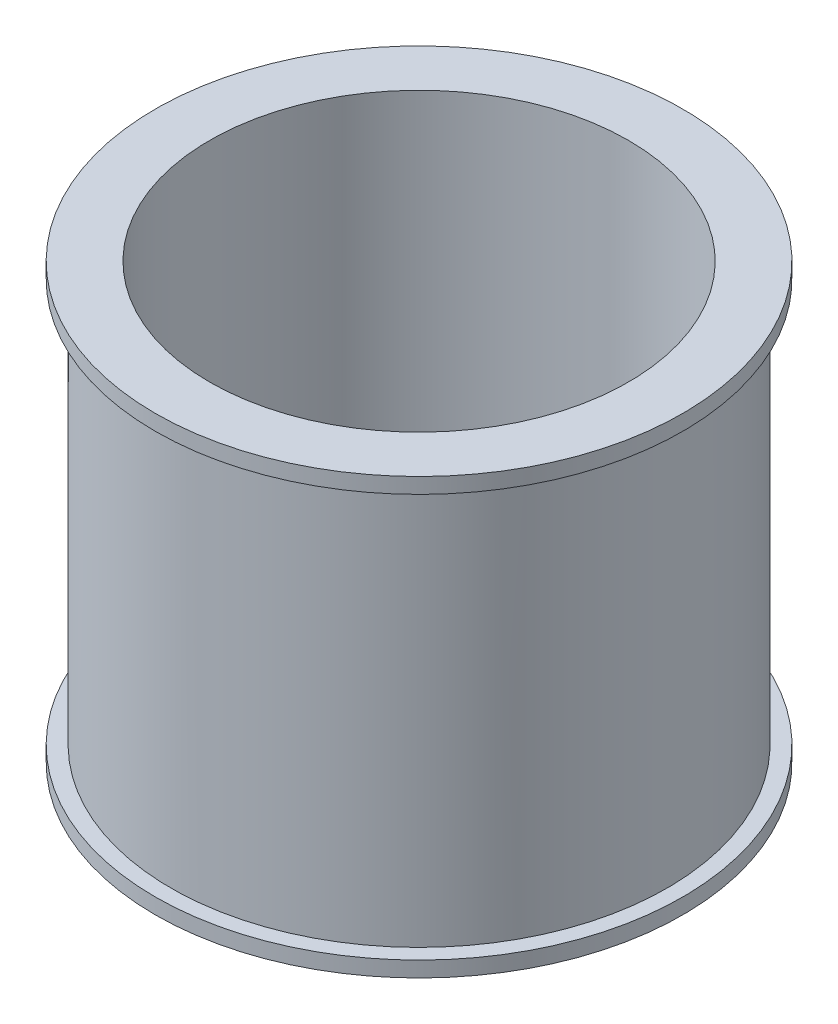
SolidWorks part; units mm, degrees
ref_plane "Front Plane" through (0, 0, 0) normal (0, 0, 1) x (1, 0, 0)
ref_plane "Top Plane" through (0, 0, 0) normal (0, 1, 0) x (1, 0, 0)
ref_plane "Right Plane" through (0, 0, 0) normal (1, 0, 0) x (0, 0, -1)
sketch "Sketch1" plane through (0, 0, 0) normal (0, 1, 0) x (1, 0, 0)
  circle A0 centre (0, 0) radius 4
  dimension "D1" = 8
extrude "Boss-Extrude1" add sketch "Sketch1" along normal blind 7
sketch "Sketch2" plane through (0, 7, 0) normal (0, 1, 0) x (1, 0, 0)
  circle A0 centre (0, 0) radius 3.375
  dimension "D1" = 6.75
extrude "Cut-Extrude1" cut sketch "Sketch2" against normal blind 10 contours A0
sketch "Sketch16" plane through (0, 7, 0) normal (0, 1, 0) x (1, 0, 0)
  circle A0 centre (0, 0) radius 4
  circle A1 centre (0, 0) radius 4.25
  dimension "D1" = 8
  dimension "D2" = 8.5
extrude "Boss-Extrude2" add sketch "Sketch16" against normal blind 0.25
ref_plane "Plane1" through (0, 3.5, 0) normal (0, 1, 0) x (1, 0, 0)
mirror "Mirror1" about plane through (0, 3.5, 0) normal (0, 1, 0) of "Boss-Extrude2"
